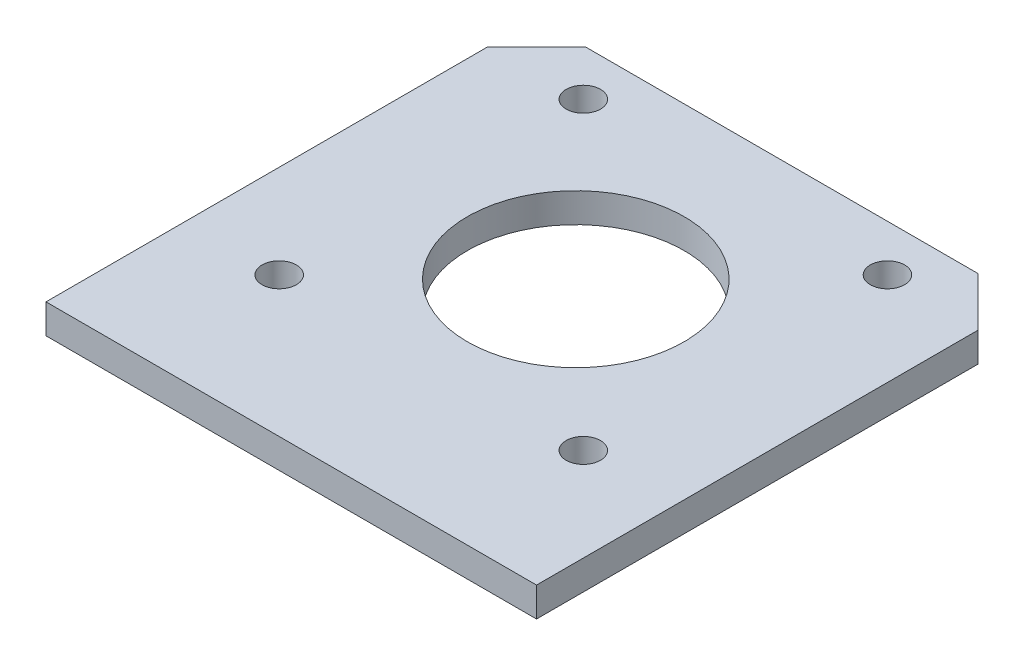
SolidWorks part; units mm, degrees
ref_plane "Plano frontal" through (0, 0, 0) normal (0, 0, 1) x (1, 0, 0)
ref_plane "Plano superior" through (0, 0, 0) normal (0, 1, 0) x (1, 0, 0)
ref_plane "Plano direito" through (0, 0, 0) normal (1, 0, 0) x (0, 0, -1)
sketch "Esboço1" plane through (0, 0, 0) normal (0, 1, 0) x (1, 0, 0)
  line L12 (-20, 21) -> (-25, 16)
  line L13 (-20, 21) -> (20, 21)
  line L14 (0, -22) -> (0, 59.6399) construction
  line L17 (-25, 16) -> (-25, -29)
  line L18 (-25, -29) -> (25, -29)
  line L19 (25, 16) -> (25, -29)
  line L20 (20, 21) -> (25, 16)
  circle A8 centre (0, 0) radius 11.05
  circle A9 centre (-15.5, 16.2709) radius 1.75
  circle A10 centre (15.5, 16.2709) radius 1.75
  circle A11 centre (-15.5, -14.7291) radius 1.75
  circle A12 centre (15.5, -14.7291) radius 1.75
  point P2 (-25, 21)
  point P5 (25, 21)
  point P11 (0, 0)
  point P18 (0, 0)
  point P19 (0, 0)
  point P20 (0, 0)
  point P21 (0, 0)
  point P22 (0, 0)
  point P23 (0, 0)
  dimension "D3" = 29
  dimension "D4" = 25
  dimension "D5" = 50
  dimension "D1" = 22.1
  dimension "D6" = 3.5
  dimension "D2" = 21
  dimension "D7" = 31
  dimension "D8" = 31
  dimension "D9" = 31
extrude "Ressalto-extrusão3" add sketch "Esboço1" along normal blind 3
